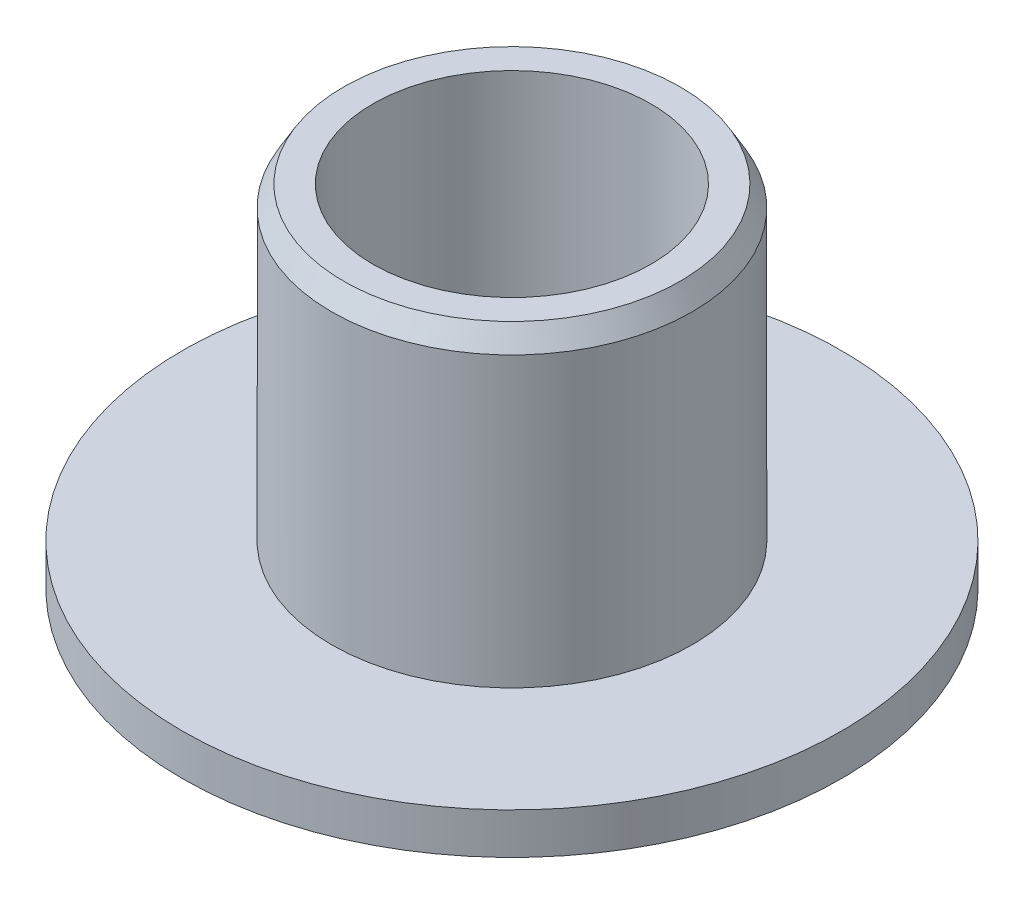
SolidWorks part; units mm, degrees
ref_plane "Front Plane" through (0, 0, 0) normal (0, 0, 1) x (1, 0, 0)
ref_plane "Top Plane" through (0, 0, 0) normal (0, 1, 0) x (1, 0, 0)
ref_plane "Right Plane" through (0, 0, 0) normal (1, 0, 0) x (0, 0, -1)
sketch "Sketch1" plane through (0, 0, 0) normal (0, 0, 1) x (1, 0, 0)
  line L0 (0, 21.623) -> (0, 0) construction
  line L1 (8.75, 2) -> (16, 2) construction
  line L2 (9, 2) -> (9, 17) construction
  line L3 (9, 17) -> (0, 17) construction
  line L4 (0, 0) -> (-1.2722, 0) construction
  line L7 (16, 2) -> (9, 2)
  line L8 (9, 2) -> (8.75, 2)
  line L11 (8.75, 17) -> (8.75, 2)
  line L12 (0, 0) -> (16, 0)
  line L13 (16, 0) -> (16, 2)
  line L15 (0, 0) -> (0, 2)
  line L16 (0, 2) -> (2.5, 2)
  line L17 (6.75, 2) -> (6.75, 5.4667)
  line L18 (6.75, 17) -> (8.75, 17)
  line L19 (6.75, 6) -> (3, 2) construction
  line L20 (3.5, 2) -> (6.75, 5.4667)
  line L21 (6.75, 6.5333) -> (2.5, 2)
  line L22 (2.5, 2) -> (3, 2) construction
  line L23 (3, 2) -> (3.5, 2) construction
  line L24 (3.5, 2) -> (6.75, 2)
  line L25 (6.75, 6.5333) -> (6.75, 17)
  line L26 (6.75, 6) -> (6.75, 6.5333) construction
  line L27 (6.75, 5.4667) -> (6.75, 6) construction
  point P16 (2.3063, 7.155)
  point P20 (3.5997, 1.8477)
  point P21 (3.7863, 2)
  point P24 (0, 0)
  point P25 (3.4686, 2)
  point P26 (0, 0)
  point P27 (3.9325, 2)
  dimension "D1" = 2
  dimension "D2" = 16
  dimension "D3" = 15
  dimension "D4" = 9
  dimension "D5" = 17.5
  dimension "D6" = 2
  dimension "D7" = 3
  dimension "D8" = 4
  dimension "D9" = 0.5
revolve "Revolve1" add sketch "Sketch1" angle 360 about L0
chamfer "Chamfer1" distance 1 angle 30 1 edges at (0, 17, 8.75)
